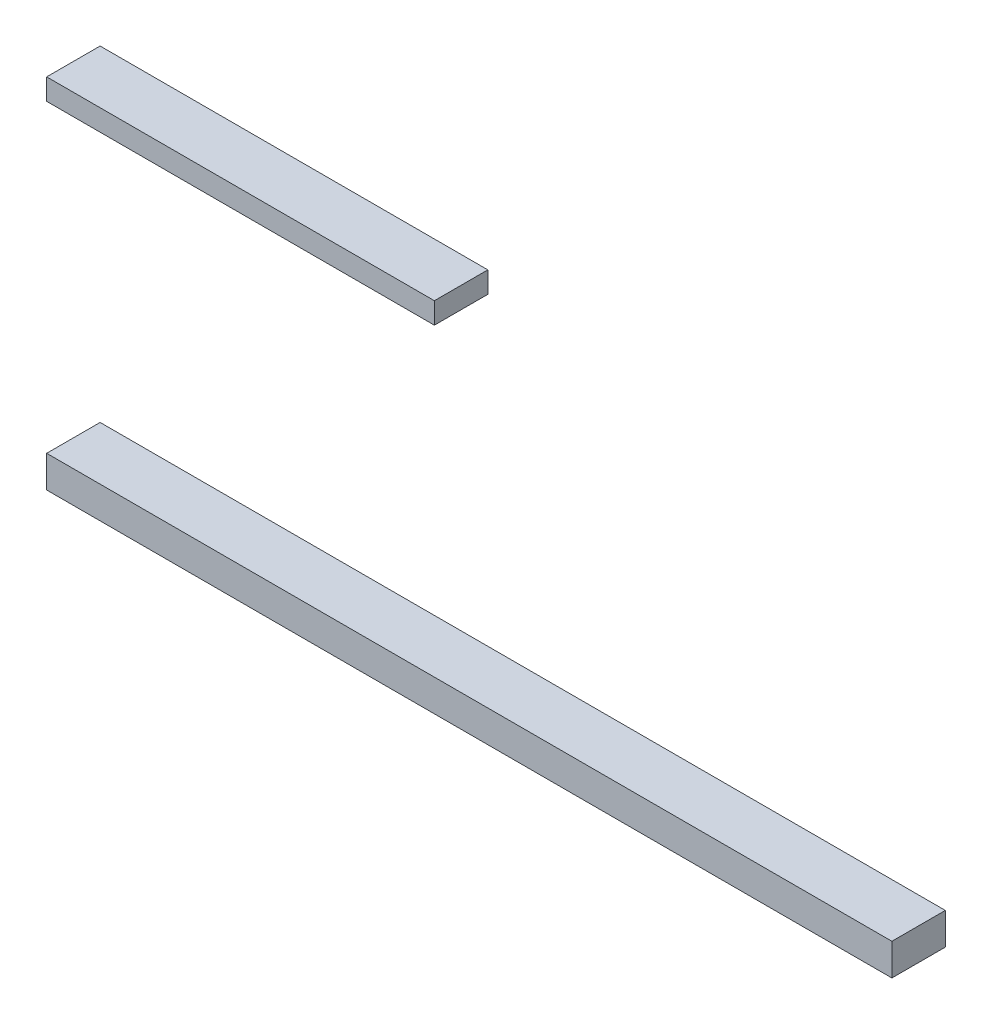
SolidWorks part; units mm, degrees
ref_plane "Спереди" through (0, 0, 0) normal (0, 0, 1) x (1, 0, 0)
ref_plane "Сверху" through (0, 0, 0) normal (0, 1, 0) x (1, 0, 0)
ref_plane "Справа" through (0, 0, 0) normal (1, 0, 0) x (0, 0, -1)
sketch "Эскиз1" plane through (0, 0, 0) normal (0, 0, 1) x (1, 0, 0)
  line L0 (3199, -203) -> (3199, -6915) construction
  line L1 (3199, -3243) -> (7184, -3243)
  line L2 (3199, -3243) -> (3199, -3393)
  line L3 (3199, -3393) -> (7184, -3393)
  line L4 (7184, -3243) -> (7184, -3393)
  line L5 (7184, -3418) -> (7184, -3218) construction
  line L6 (7924, -3218) -> (6984, -3218) construction
  line L7 (3199, -1706) -> (5027, -1706)
  line L8 (3199, -1706) -> (3199, -1806)
  line L9 (3199, -1806) -> (5027, -1806)
  line L10 (5027, -1706) -> (5027, -1806)
  dimension "D1" = 150
  dimension "D2" = 25
extrude "Бобышка-Вытянуть1" add sketch "Эскиз1" along normal up to surface (252 mm away)
